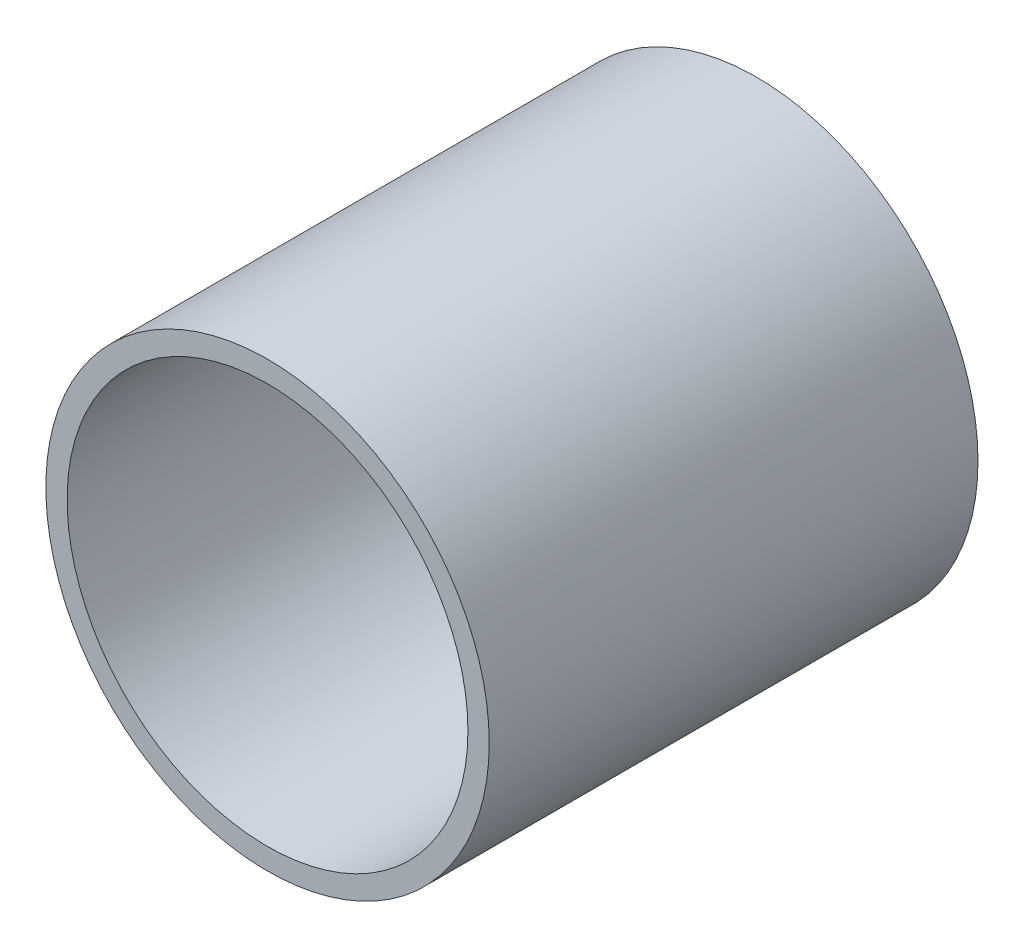
SolidWorks part; units mm, degrees
ref_plane "Front Plane" through (0, 0, 0) normal (0, 0, 1) x (1, 0, 0)
ref_plane "Top Plane" through (0, 0, 0) normal (0, 1, 0) x (1, 0, 0)
ref_plane "Right Plane" through (0, 0, 0) normal (1, 0, 0) x (0, 0, -1)
sketch "Sketch1" plane through (0, 0, 0) normal (0, 0, 1) x (1, 0, 0)
  circle A0 centre (0, 0) radius 31.75
  circle A1 centre (0, 0) radius 28.7
  dimension "D1" = 63.5
  dimension "D2" = 3.05
extrude "Boss-Extrude1" add sketch "Sketch1" along normal blind 70
